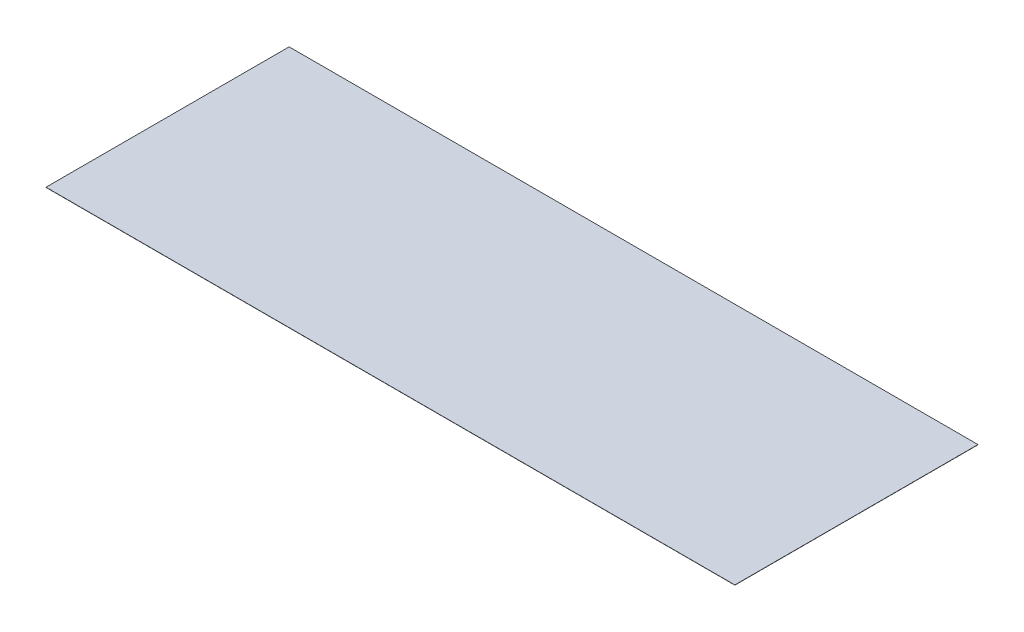
SolidWorks part; units mm, degrees
ref_plane "Front Plane" through (0, 0, 0) normal (0, 0, 1) x (1, 0, 0)
ref_plane "Top Plane" through (0, 0, 0) normal (0, 1, 0) x (1, 0, 0)
ref_plane "Right Plane" through (0, 0, 0) normal (1, 0, 0) x (0, 0, -1)
sketch "Sketch1" plane through (0, 0, 0) normal (0, 1, 0) x (1, 0, 0)
  line L0 (8500, -3000) -> (8500, 3000) construction
  line L1 (-8500, -3000) -> (8500, -3000) construction
  line L2 (-8500, 3000) -> (8500, 3000) construction
  line L3 (-8500, -3000) -> (-8500, 3000) construction
  line L4 (8500, -3000) -> (8500, 3000)
  line L5 (-8500, -3000) -> (8500, -3000)
  line L6 (-8500, 3000) -> (8500, 3000)
  line L7 (-8500, -3000) -> (-8500, 3000)
extrude "Boss-Extrude1" add sketch "Sketch1" against normal blind 5
